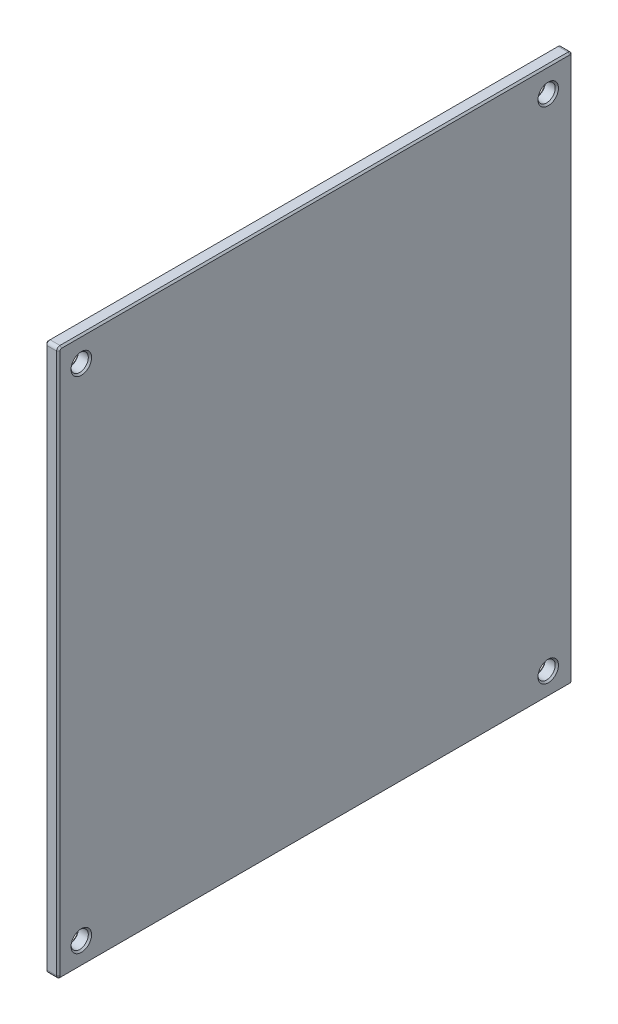
SolidWorks part; units mm, degrees
ref_plane "前视基准面" through (0, 0, 0) normal (0, 0, 1) x (1, 0, 0)
ref_plane "上视基准面" through (0, 0, 0) normal (0, 1, 0) x (1, 0, 0)
ref_plane "右视基准面" through (0, 0, 0) normal (1, 0, 0) x (0, 0, -1)
other "Configuration Table"
sketch "草图1" plane through (0, 0, 0) normal (1, 0, 0) x (0, 0, -1)
  line L1 (0, 0) -> (65.8, 0)
  line L2 (0, 0) -> (0, -69.8)
  line L3 (0, -69.8) -> (65.8, -69.8)
  line L4 (65.8, 0) -> (65.8, -69.8)
  dimension "D1" = 65.8
  dimension "D2" = 69.8
extrude "凸台-拉伸1" add sketch "草图1" along normal blind 1.6
sketch "草图2" plane through (1.6, 0, 0) normal (1, 0, 0) x (0, 0, -1)
  line L0 (65.8, 0) -> (0, 0) construction
  line L1 (65.8, -69.8) -> (65.8, 0) construction
  circle A0 centre (61.2, -4.6) radius 1.05
  circle A1 centre (4.4, -4.6) radius 1.05
  circle A2 centre (4.4, -65.4) radius 1.05
  circle A3 centre (61.2, -65.4) radius 1.05
  dimension "D1" = 2.1
  dimension "D2" = 4.6
  dimension "D3" = 4.6
  dimension "D4" = 2
  dimension "D5" = 2
extrude "切除-拉伸1" cut sketch "草图2" against normal blind 1.6
sketch "草图5" plane through (0, 0, 0) normal (-1, 0, 0) x (0, 0, 1)
  line L0 (-64.2, -1.6) -> (-64.2, -68.2)
  line L1 (-65.8, 0) -> (0, 0)
  line L2 (-65.8, 0) -> (-65.8, -69.8)
  line L3 (-65.8, -69.8) -> (0, -69.8)
  line L4 (0, 0) -> (0, -69.8)
  line L5 (-64.2, -68.2) -> (-1.6, -68.2)
  line L6 (-1.6, -1.6) -> (-1.6, -68.2)
  line L7 (-64.2, -1.6) -> (-1.6, -1.6)
  dimension "D1" = 1.6
extrude "切除-拉伸2" cut sketch "草图5" against normal blind 1.6
fillet "圆角2" radius 0.4 4 edges at (0.8, -1.6, -1.6) (0.8, -68.2, -1.6) (0.8, -68.2, -64.2) (0.8, -1.6, -64.2)
chamfer "倒角1" distance 0.2 angle 45 24 edges at (0, -4.6, -62.25) (0, -4.6, -5.45) (0, -65.4, -5.45) (0, -65.4, -62.25) (1.6, -4.6, -62.25) (1.6, -4.6, -5.45) (1.6, -65.4, -5.45) (1.6, -65.4, -62.25) (0, -34.9, -1.6) (0, -68.2, -32.9) (0, -34.9, -64.2) (0, -1.6, -32.9) (1.6, -68.2, -32.9) (1.6, -34.9, -1.6) (1.6, -1.6, -32.9) (1.6, -34.9, -64.2) (0, -68.0828, -1.7172) (0, -68.0828, -64.0828) (0, -1.7172, -64.0828) (0, -1.7172, -1.7172) (1.6, -1.7172, -64.0828) (1.6, -68.0828, -64.0828) (1.6, -68.0828, -1.7172) (1.6, -1.7172, -1.7172)
